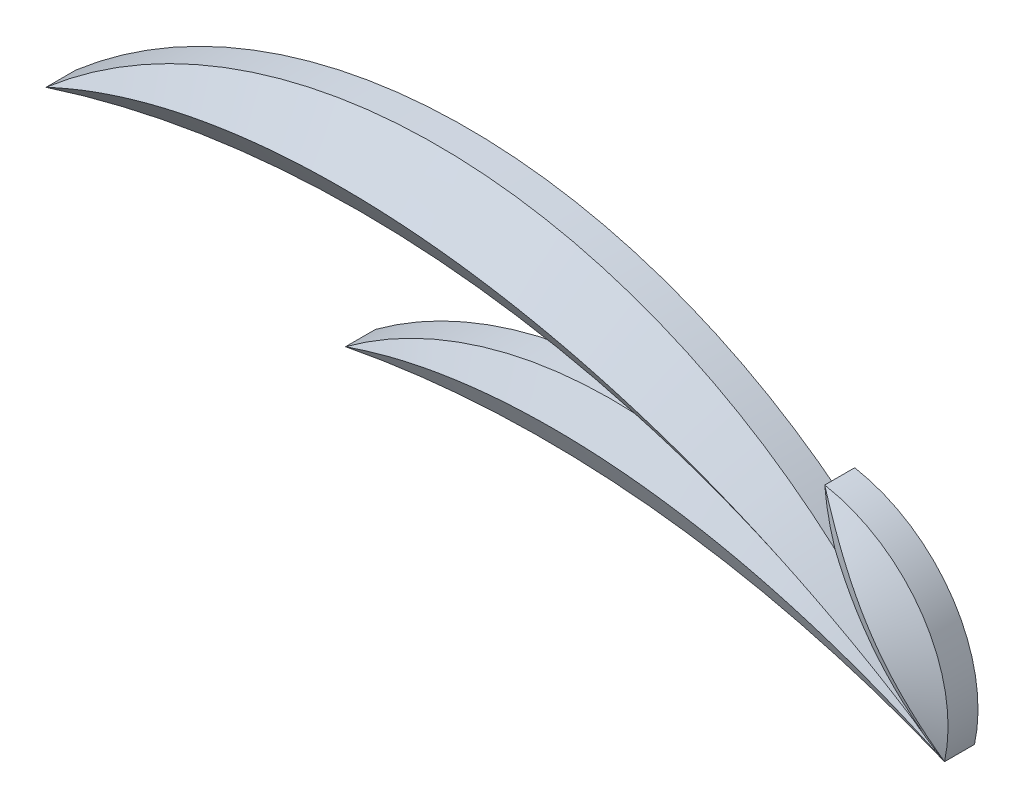
SolidWorks part; units mm, degrees
ref_plane "Plano frontal" through (0, 0, 0) normal (0, 0, 1) x (1, 0, 0)
ref_plane "Plano superior" through (0, 0, 0) normal (0, 1, 0) x (1, 0, 0)
ref_plane "Plano direito" through (0, 0, 0) normal (1, 0, 0) x (0, 0, -1)
sketch "Esboço1" plane through (0, 0, 0) normal (0, 0, 1) x (1, 0, 0)
  spline S0 degree 2 poles (0, 0) (-18.1517, 12.2016) (-40, 4) knots 0 0 0 1 1 1 construction
  spline S1 degree 3 poles (0, 0) (-13.7782, 18.1009) (-41.168, 18.842) (-60, 9) knots 0 0 0 0 1 1 1 1 construction
  spline S2 degree 2 poles (0, 0) (-1.9597, 7.2357) (-8, 12) knots 0 0 0 1 1 1 construction
  point P11 (0, 0)
  point P14 (-1.4376, 7.0745)
  point P15 (-7.4202, 13.261)
  dimension "D1" = 2
  dimension "D2" = 8
  dimension "D3" = 13
  dimension "D4" = 16
  dimension "D5" = 40
  dimension "D6" = 50
  dimension "D7" = 60
  dimension "D8" = 4
  dimension "D9" = 5
  dimension "D10" = 6
  dimension "D11" = 9
  dimension "D12" = 12
  dimension "D13" = 12
  dimension "D14" = 13
sketch "Esboço2" plane through (0, 0, 0) normal (0, 0, 1) x (1, 0, 0)
  arc A6 (0, 0) -> (-8, 12) centre (-9.7646, 2.1569) ccw
  arc A7 (0, 0) -> (-8, 12) centre (6.9439, 13.2959) cw
  arc A8 (-60, 9) -> (0, 0) centre (-33.8675, -21.2836) cw
  arc A9 (-60, 9) -> (0, 0) centre (-39.0278, -55.6851) cw
  arc A10 (-40, 4) -> (0, 0) centre (-22.2161, -20.1605) cw
  arc A11 (-40, 4) -> (0, 0) centre (-26.6719, -64.7195) cw
  dimension "D1" = 10
  dimension "D2" = 15
  dimension "D3" = 40
  dimension "D4" = 68
  dimension "D5" = 30
  dimension "D6" = 70
sketch "Esboço3" plane through (0, 0, 0) normal (0, 0, 1) x (1, 0, 0)
  arc A0 (-8, 12) -> (0, 0) centre (-9.7646, 2.1569) cw
  arc A1 (-8, 12) -> (0, 0) centre (6.9439, 13.2959) ccw
  arc A4 (0, 0) -> (-8, 12) centre (-9.7646, 2.1569) ccw construction
  arc A5 (-8, 12) -> (0, 0) centre (6.9439, 13.2959) ccw construction
extrude "Ressalto-extrusão1" add sketch "Esboço3" along normal blind 15 draft 60
sketch "Esboço4" plane through (0, 0, 0) normal (0, 0, 1) x (1, 0, 0)
  arc A0 (-60, 9) -> (0, 0) centre (-33.8675, -21.2836) cw
  arc A1 (-60, 9) -> (0, 0) centre (-39.0278, -55.6851) cw
  arc A4 (0, 0) -> (-60, 9) centre (-33.8675, -21.2836) ccw construction
  arc A5 (0, 0) -> (-60, 9) centre (-39.0278, -55.6851) ccw construction
extrude "Ressalto-extrusão2" add sketch "Esboço4" along normal blind 5 draft 53
sketch "Esboço5" plane through (0, 0, 0) normal (0, 0, 1) x (1, 0, 0)
  arc A0 (-40, 4) -> (0, 0) centre (-22.2161, -20.1605) cw
  arc A1 (-40, 4) -> (0, 0) centre (-26.6719, -64.7195) cw
  arc A4 (0, 0) -> (-40, 4) centre (-22.2161, -20.1605) ccw construction
  arc A5 (0, 0) -> (-40, 4) centre (-26.6719, -64.7195) ccw construction
extrude "Ressalto-extrusão3" add sketch "Esboço5" along normal blind 5 draft 60
sketch "Esboço6" plane through (0, 0, 0) normal (0, 0, 1) x (1, 0, 0)
  arc A0 (0, 0) -> (-8, 12) centre (-9.7646, 2.1569) ccw
  arc A1 (-7.3118, 8.6295) -> (-8, 12) centre (6.9439, 13.2959) cw
  arc A2 (-60, 9) -> (-7.3118, 8.6295) centre (-33.8675, -21.2836) cw
  arc A3 (-60, 9) -> (-20.7119, 9.8017) centre (-39.0278, -55.6851) cw
  arc A4 (-20.7119, 9.8017) -> (-40, 4) centre (-22.2161, -20.1605) ccw
  arc A5 (-40, 4) -> (0, 0) centre (-26.6719, -64.7195) cw
  arc A6 (0, 0) -> (-8, 12) centre (-9.7646, 2.1569) ccw construction
  arc A13 (-8, 12) -> (-7.3118, 8.6295) centre (6.9439, 13.2959) ccw construction
  arc A14 (-7.3118, 8.6295) -> (-60, 9) centre (-33.8675, -21.2836) ccw construction
  arc A15 (-20.7119, 9.8017) -> (-60, 9) centre (-39.0278, -55.6851) ccw construction
  arc A16 (-20.7119, 9.8017) -> (-40, 4) centre (-22.2161, -20.1605) ccw construction
  arc A17 (0, 0) -> (-40, 4) centre (-26.6719, -64.7195) ccw construction
extrude "Ressalto-extrusão4" add sketch "Esboço6" against normal blind 2
